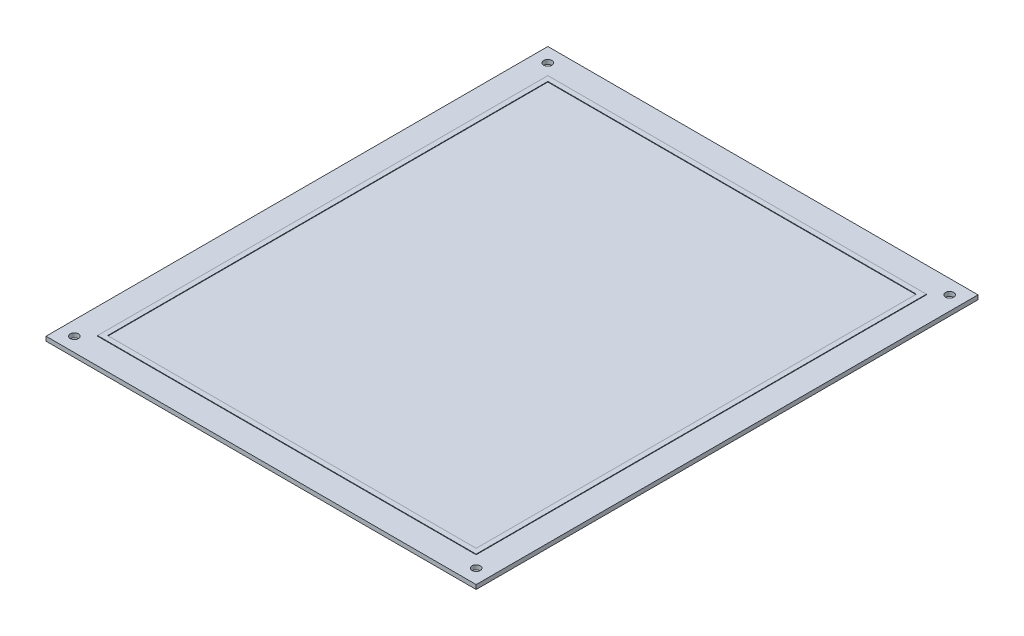
SolidWorks part; units mm, degrees
ref_plane "Front Plane" through (0, 0, 0) normal (0, 0, 1) x (1, 0, 0)
ref_plane "Top Plane" through (0, 0, 0) normal (0, 1, 0) x (1, 0, 0)
ref_plane "Right Plane" through (0, 0, 0) normal (1, 0, 0) x (0, 0, -1)
sketch "Sketch1" plane through (0, 0, 0) normal (0, 1, 0) x (1, 0, 0)
  line L1 (-150, -175) -> (150, -175)
  line L2 (-150, -175) -> (-150, 175)
  line L3 (-150, 175) -> (150, 175)
  line L4 (150, -175) -> (150, 175)
  circle A0 centre (140.1, 165.1) radius 2.88
  circle A1 centre (-140.1, 165.1) radius 2.88
  circle A2 centre (140.1, -165.1) radius 2.88
  circle A3 centre (-140.1, -165.1) radius 2.88
extrude "Electronics tray structural panel" add sketch "Sketch1" along normal mid plane 3
sketch "Sketch2" plane through (0, 0, 0) normal (0, 1, 0) x (1, 0, 0)
  line L1 (-132, -157) -> (132, -157)
  line L2 (-132, -157) -> (-132, 157)
  line L3 (-132, 157) -> (132, 157)
  line L4 (132, -157) -> (132, 157)
  line L5 (-128.5, -153.5) -> (128.5, -153.5)
  line L6 (-128.5, -153.5) -> (-128.5, 153.5)
  line L7 (-128.5, 153.5) -> (128.5, 153.5)
  line L8 (128.5, -153.5) -> (128.5, 153.5)
extrude "Electronics tray structural panel inset stiffener" add sketch "Sketch2" along normal mid plane 3.8
sketch "Sketch3" plane through (0, 0, 0) normal (0, 1, 0) x (1, 0, 0)
  circle A0 centre (140.1, 165.1) radius 2.88
  circle A1 centre (-140.1, 165.1) radius 2.88
  circle A2 centre (140.1, -165.1) radius 2.88
  circle A3 centre (-140.1, -165.1) radius 2.88
